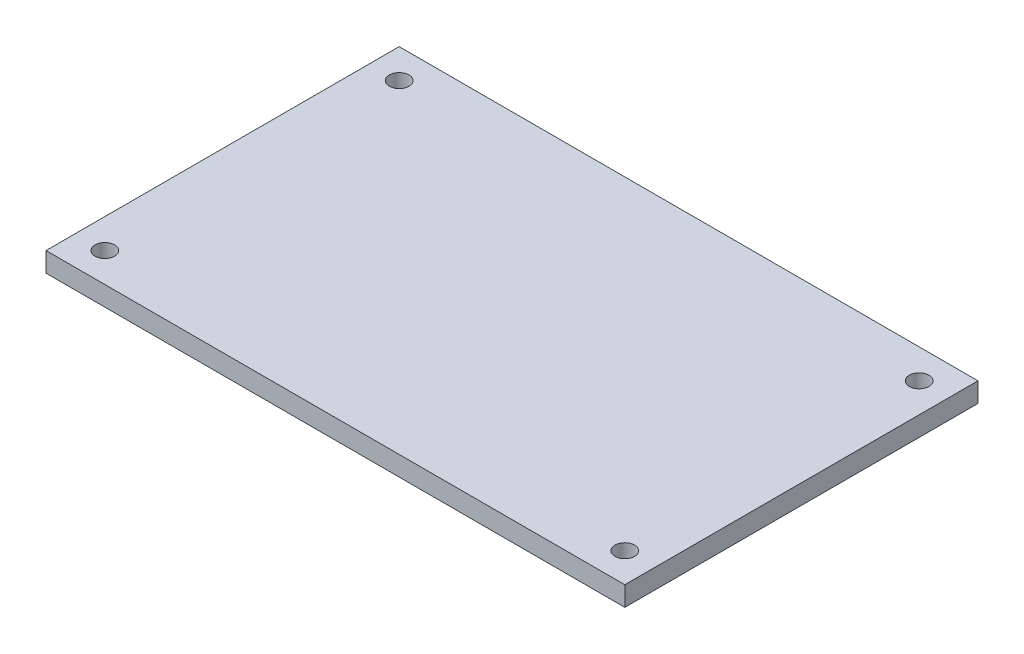
SolidWorks part; units mm, degrees
ref_plane "Front Plane" through (0, 0, 0) normal (0, 0, 1) x (1, 0, 0)
ref_plane "Top Plane" through (0, 0, 0) normal (0, 1, 0) x (1, 0, 0)
ref_plane "Right Plane" through (0, 0, 0) normal (1, 0, 0) x (0, 0, -1)
sketch "Sketch1" plane through (0, 0, 0) normal (0, 1, 0) x (1, 0, 0)
  line L1 (-187.325, 114.3) -> (187.325, 114.3)
  line L2 (-187.325, 114.3) -> (-187.325, -114.3)
  line L3 (-187.325, -114.3) -> (187.325, -114.3)
  line L4 (187.325, 114.3) -> (187.325, -114.3)
  line L5 (-187.325, 114.3) -> (187.325, -114.3) construction
  line L6 (-187.325, -114.3) -> (187.325, 114.3) construction
  point P0 (0, 0)
  dimension "D1" = 228.6
  dimension "D2" = 374.65
extrude "Boss-Extrude1" add sketch "Sketch1" along normal blind 12.7
hole_wizard "1/2 (0.5000) Dowel Hole1" positions "Sketch4" profile "Sketch3" hole size "1/2" standard "ANSI Inch"
sketch "Sketch4" plane through (0, 12.7, 0) normal (0, 1, 0) x (1, 0, 0)
  line L1 (187.325, 114.3) -> (-187.325, 114.3) construction
  line L2 (-187.325, 114.3) -> (-187.325, -114.3) construction
  line L3 (187.325, -114.3) -> (187.325, 114.3) construction
  line L4 (-187.325, -114.3) -> (187.325, -114.3) construction
  point P0 (-168.275, 95.25)
  point P2 (-168.275, -95.25)
  point P4 (168.275, -95.25)
  point P6 (168.275, 95.25)
  dimension "D1" = 19.05
  dimension "D2" = 19.05
  dimension "D3" = 19.05
  dimension "D4" = 19.05
sketch "Sketch3" plane through (-168.275, 12.7, -95.25) normal (1, 0, 0) x (0, 0, 1)
  line L0 (0, 0) -> (0, 16.5155)
  line L1 (0, 16.5155) -> (6.35, 12.7)
  line L2 (6.35, 12.7) -> (6.35, 0)
  line L5 (6.35, 0) -> (0, 0)
  line L10 (0, 16.5155) -> (-6.35, 12.7) construction
  line L11 (0, -6.35) -> (0, 107.95) construction
  dimension "Hole Dia." = 12.7
  dimension "Hole Depth" = 12.7
  dimension "Drill Angle" = 118
